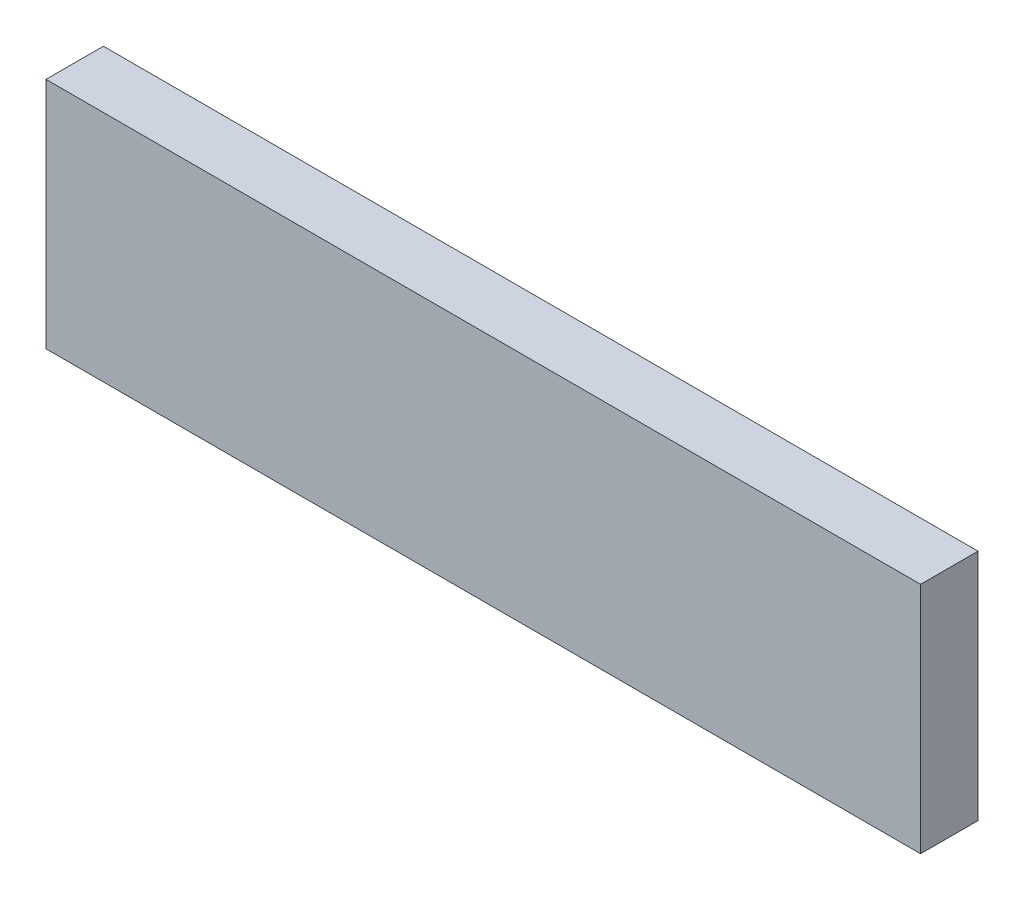
SolidWorks part; units mm, degrees
ref_plane "Front Plane" through (0, 0, 0) normal (1, 0, 0) x (0, 1, 0)
ref_plane "Top Plane" through (0, 0, 0) normal (0, 0, 1) x (0, 1, 0)
ref_plane "Right Plane" through (0, 0, 0) normal (0, 1, 0) x (-1, 0, 0)
sketch "Sketch1" plane through (35, 0, 0) normal (1, 0, 0) x (0, 0, -1)
  line L1 (-20.5473, -33.2918) -> (-18.2503, -33.2918)
  line L2 (-20.5473, -33.2918) -> (-20.5473, -42.6301)
  line L3 (-20.5473, -42.6301) -> (-18.2503, -42.6301)
  line L4 (-18.2503, -33.2918) -> (-18.2503, -42.6301)
extrude "Boss-Extrude1" add sketch "Sketch1" along normal blind 35
